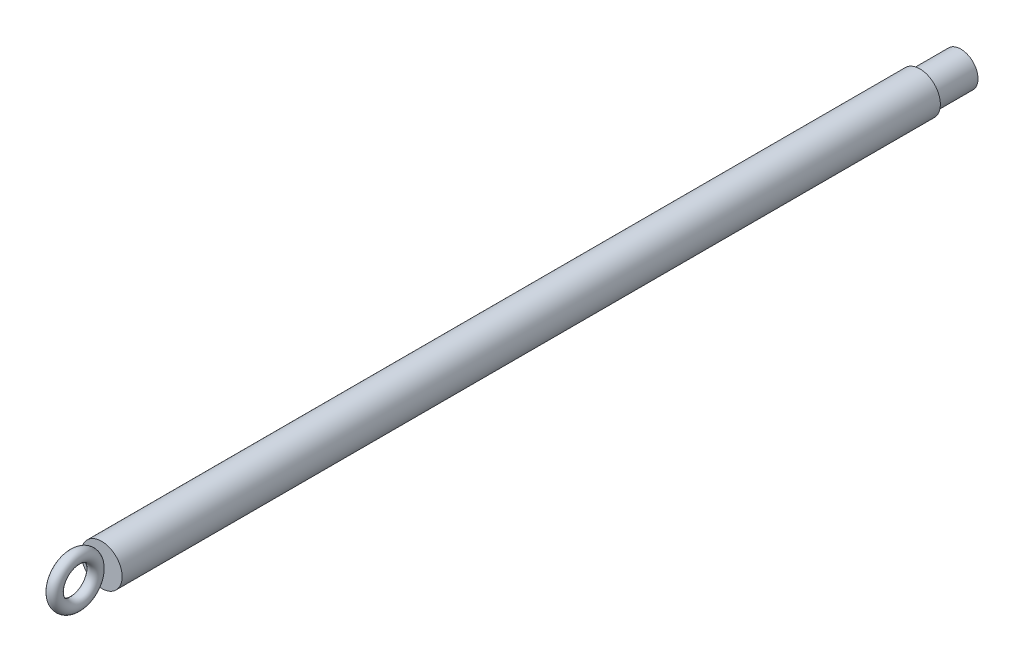
SolidWorks part; units mm, degrees
material "6061 Alloy"
ref_plane "Front Plane" through (0, 0, 0) normal (0, 0, 1) x (1, 0, 0)
ref_plane "Top Plane" through (0, 0, 0) normal (0, 1, 0) x (1, 0, 0)
ref_plane "Right Plane" through (0, 0, 0) normal (1, 0, 0) x (0, 0, -1)
sketch "Sketch1" plane through (0, 0, 0) normal (0, 0, 1) x (1, 0, 0)
  circle A0 centre (0, 0) radius 2.1
  dimension "D1" = 4.2
extrude "Boss-Extrude1" add sketch "Sketch1" along normal blind 5
sketch "Sketch2" plane through (0, 0, 5) normal (0, 0, 1) x (1, 0, 0)
  circle A0 centre (0, 0) radius 2.5
  dimension "D1" = 5
extrude "Boss-Extrude2" add sketch "Sketch2" along normal blind 100
sketch "Sketch6" plane through (0, 0, 0) normal (0, 1, 0) x (1, 0, 0)
  line L1 (-2.5, -105) -> (2.5, -105) construction
  circle A0 centre (0, -105.75) radius 0.75
  dimension "D1" = 1.5
sketch "Sketch3" plane through (0, 0, 0) normal (1, 0, 0) x (0, 0, -1)
  line L1 (-105, 0) -> (-106.5, 0) construction
  line L2 (-105.75, 0) -> (-105.75, -0.5216) construction
  circle A0 centre (-108.25, 0) radius 2.5
  dimension "D1" = 5
sweep "Sweep1" add profiles "Sketch6" path "Sketch3"
